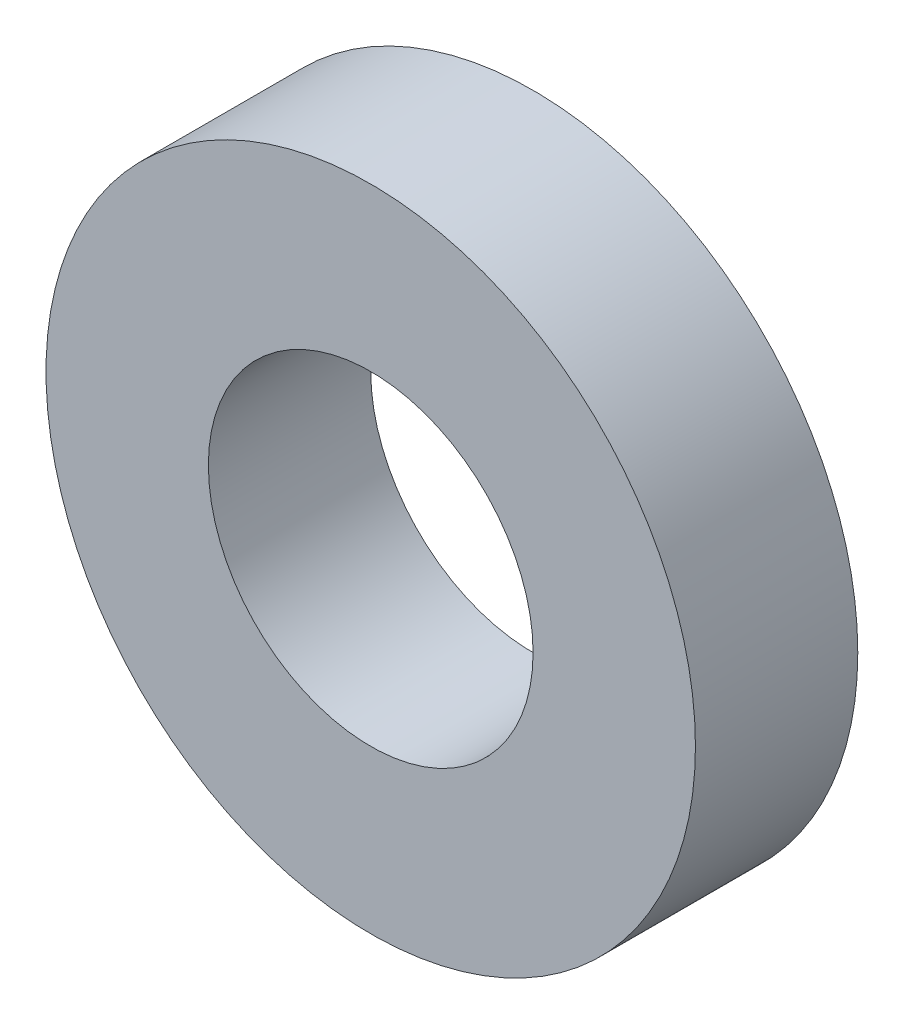
SolidWorks part; units mm, degrees
ref_plane "Front Plane" through (0, 0, 0) normal (0, 0, 1) x (1, 0, 0)
ref_plane "Top Plane" through (0, 0, 0) normal (0, 1, 0) x (1, 0, 0)
ref_plane "Right Plane" through (0, 0, 0) normal (1, 0, 0) x (0, 0, -1)
sketch "Sketch1" plane through (0, 0, 0) normal (0, 0, 1) x (1, 0, 0)
  circle A0 centre (0, 0) radius 5
  circle A1 centre (0, 0) radius 10
  dimension "D1" = 10
  dimension "D2" = 20
extrude "Boss-Extrude1" add sketch "Sketch1" along normal blind 5
